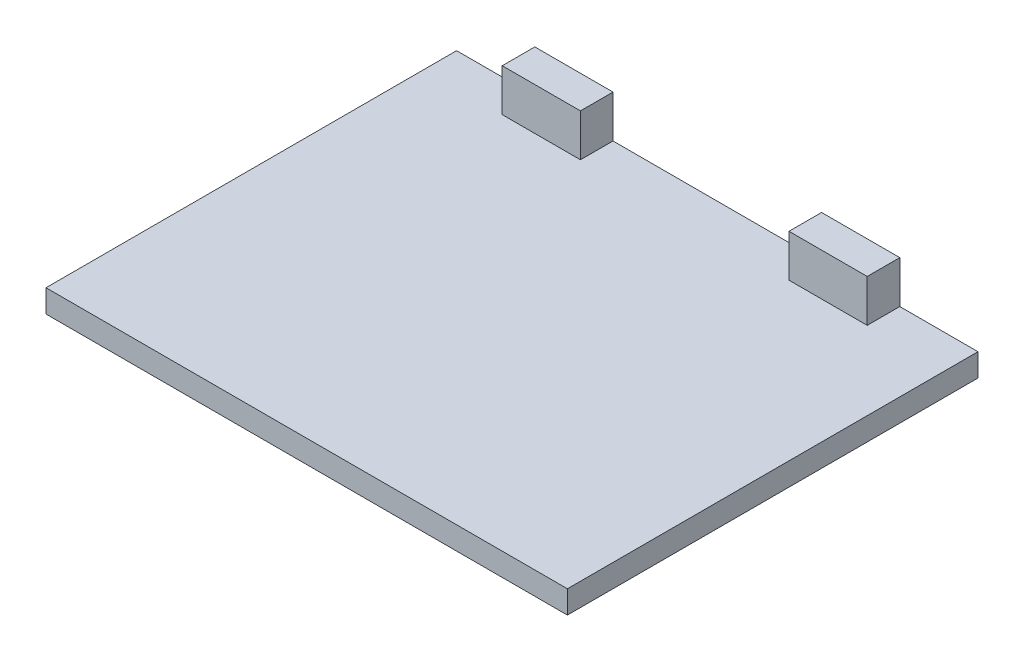
SolidWorks part; units mm, degrees
ref_plane "Front Plane" through (0, 0, 0) normal (0, 0, 1) x (1, 0, 0)
ref_plane "Top Plane" through (0, 0, 0) normal (0, 1, 0) x (1, 0, 0)
ref_plane "Right Plane" through (0, 0, 0) normal (1, 0, 0) x (0, 0, -1)
sketch "Sketch1" plane through (0, 0, 0) normal (0, 1, 0) x (1, 0, 0)
  line L1 (0, 0) -> (80, 0)
  line L2 (0, 0) -> (0, 58)
  line L3 (0, 58) -> (80, 58)
  line L4 (80, 0) -> (80, 58)
  dimension "D1" = 80
  dimension "D2" = 58
extrude "Boss-Extrude1" add sketch "Sketch1" along normal blind 3.5
sketch "Sketch2" plane through (0, 0, -58) normal (0, 0, -1) x (-1, 0, 0)
  line L0 (-80, 3.5) -> (0, 3.5) construction
  line L1 (-80, 3.5) -> (0, 3.5)
  line L2 (-80, 3.5) -> (-80, 0) construction
  line L3 (-80, 3.5) -> (-80, 0)
  line L4 (-80, 0) -> (0, 0) construction
  line L5 (-80, 0) -> (0, 0)
  line L6 (0, 3.5) -> (0, 0) construction
  line L7 (0, 3.5) -> (0, 0)
  line L8 (-40, 0) -> (-40, 10) construction
  line L9 (-68, 0) -> (-56, 0)
  line L10 (-68, 0) -> (-68, 10)
  line L11 (-68, 10) -> (-56, 10)
  line L12 (-56, 0) -> (-56, 10)
  line L13 (-12, 0) -> (-12, 10)
  line L14 (-24, 0) -> (-24, 10)
  line L15 (-12, 10) -> (-24, 10)
  point P10 (0, 0)
  dimension "D1" = 10
  dimension "D2" = 16
  dimension "D3" = 12
extrude "Boss-Extrude2" add sketch "Sketch2" along normal blind 5 contours L14 L5 L13 L1 | L13 L15 L14 L1 | L5 L12 L1 L10 | L1 L12 L11 L10
